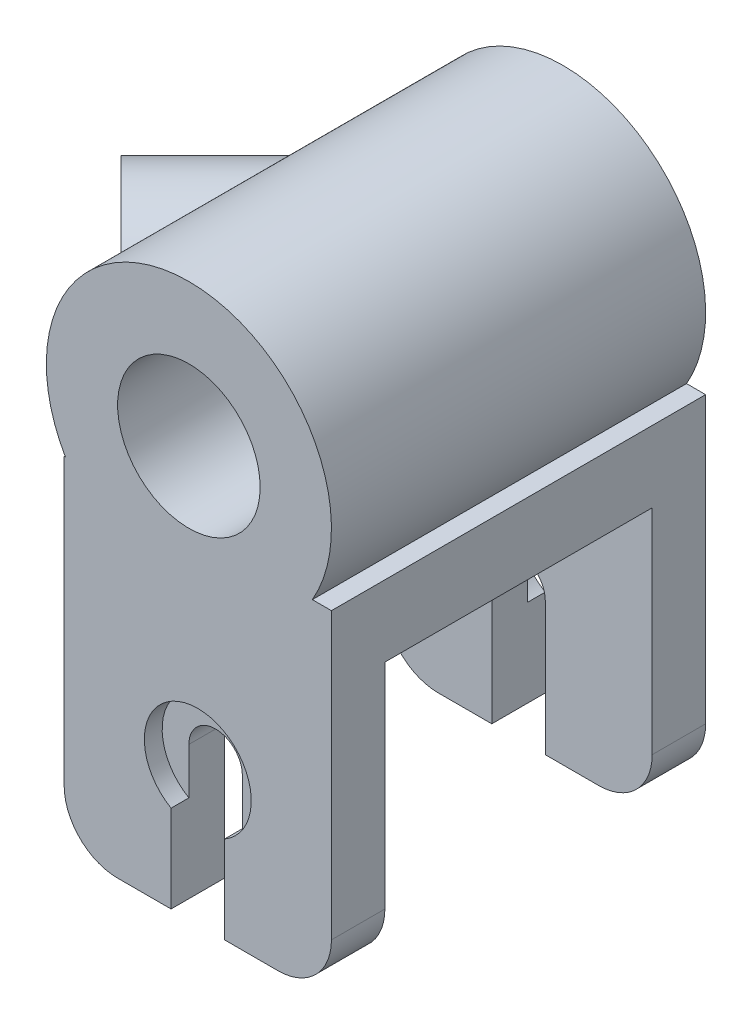
SolidWorks part; units mm, degrees
ref_plane "Спереди" through (0, 0, 0) normal (0, 0, 1) x (1, 0, 0)
ref_plane "Сверху" through (0, 0, 0) normal (0, 1, 0) x (1, 0, 0)
ref_plane "Справа" through (0, 0, 0) normal (1, 0, 0) x (0, 0, -1)
sketch "Sketch1" plane through (0, 0, 0) normal (0, 0, 1) x (1, 0, 0)
  line L0 (-7, -8) -> (8, -8)
  line L1 (-7, -4) -> (-6.9282, -4)
  line L2 (8, -8) -> (8, -4)
  line L3 (-7.3846, -3.0769) -> (-7, -4)
  line L4 (-7, -4) -> (-7, -8)
  line L5 (6.9282, -4) -> (8, -4)
  circle A0 centre (0, 0) radius 4
  arc A1 (6.9282, -4) -> (-6.9282, -4) centre (0, 0) ccw
  point P10 (-7.1344, -4)
  dimension "D1" = 8
  dimension "D2" = 4
  dimension "D3" = 15
extrude "Boss-Extrude1" add sketch "Sketch1" along normal blind 21 contours A1 L1 L4 L0 L2 L5 A0
sketch "Sketch3" plane through (0, -8, 0) normal (0, -1, 0) x (1, 0, 0)
  line L0 (-7, 21) -> (-7, 0) construction
  line L1 (8, 21) -> (-7, 21)
  line L2 (8, 21) -> (8, 18)
  line L3 (8, 18) -> (-7, 18)
  line L4 (-7, 21) -> (-7, 18)
  line L5 (8, 10.5) -> (2.9288, 10.5) construction
  line L6 (8, 21) -> (8, 0) construction
  line L7 (-7, 0) -> (-7, 3)
  line L8 (8, 3) -> (-7, 3)
  line L9 (8, 0) -> (8, 3)
  line L10 (8, 0) -> (-7, 0)
  dimension "D1" = 3
extrude "Boss-Extrude2" add sketch "Sketch3" along normal blind 15
sketch "Sketch4" plane through (0, 0, 21) normal (0, 0, 1) x (1, 0, 0)
  line L0 (0.5, -23) -> (0.5, -15.5) construction
  line L1 (8, -23) -> (-7, -23) construction
  line L2 (3.5, -15.5) -> (3.5, -23)
  line L3 (-2.5, -15.5) -> (-2.5, -23)
  line L4 (-2.5, -23) -> (3.5, -23)
  circle A0 centre (0.5, -15.5) radius 3
  dimension "D1" = 6
  dimension "D2" = 7.5
extrude "Cut-Extrude1" cut sketch "Sketch4" against normal blind 1
sketch "Sketch5" plane through (0, 0, 20) normal (0, 0, 1) x (1, 0, 0)
  line L0 (2, -15.5) -> (2, -23)
  line L1 (8, -23) -> (-7, -23) construction
  line L2 (-1, -15.5) -> (-1, -23)
  line L3 (-1, -23) -> (2, -23)
  circle A1 centre (0.5, -15.5) radius 1.5
  circle M6 centre (0.5, -15.5) radius 3
  dimension "D1" = 3
extrude "Cut-Extrude2" cut sketch "Sketch5" against normal blind 4 and the other way blind 4 contours A1 | A1 L2 L0 M6 | L2 L3 L0 M6
ref_plane "Plane1" through (0, 0, 10.5) normal (0, 0, 1) x (1, 0, 0)
mirror "Mirror1" about plane through (0, 0, 10.5) normal (0, 0, 1) of "Cut-Extrude2", "Cut-Extrude1"
fillet "Fillet1" radius 3 4 edges at (8, -23, 1.5) (-7, -23, 1.5) (-7, -23, 19.5) (8, -23, 19.5)
sketch "Sketch6" plane through (0, 0, 0) normal (0, 1, 0) x (1, 0, 0)
  line L0 (0, 0) -> (0, -25.5673) construction
  line L1 (0, -5) -> (-14.8681, -19.8681) construction
  line L2 (8, 0) -> (-8, 0) construction
  line L3 (-9.8995, -14.8995) -> (-6.364, -18.435)
  line L4 (-6.364, -18.435) -> (0, -12.0711)
  line L5 (0, -12.0711) -> (-3.5355, -8.5355)
  line L6 (-3.5355, -8.5355) -> (-9.8995, -14.8995)
  dimension "D1" = 45
  dimension "D2" = 5
  dimension "D3" = 5
  dimension "D4" = 14
revolve "Revolve1" add sketch "Sketch6" angle 360 about L1
sketch "Sketch7" plane through (0, 0, 21) normal (0, 0, 1) x (1, 0, 0)
  circle A0 centre (0, 0) radius 4
extrude "Cut-Extrude3" cut sketch "Sketch7" against normal blind 27
sketch "Sketch8" plane through (-12.3995, 0, 12.3995) normal (-0.7071, 0, 0.7071) x (0.7071, 0, 0.7071)
  circle A0 centre (3.5355, 0) radius 1.5
  dimension "D1" = 3
extrude "Cut-Extrude4" cut sketch "Sketch8" against normal blind 14
ref_plane "Plane2" through (-10.2782, 0, 10.2782) normal (-0.7071, 0, 0.7071) x (0.7071, 0, 0.7071)
sketch "Sketch9" plane through (-10.2782, 0, 10.2782) normal (-0.7071, 0, 0.7071) x (0.7071, 0, 0.7071)
  line L0 (1.919, 2.8) -> (-2.9261, 2.8)
  line L1 (6.7687, 0) -> (5.1521, 2.8)
  line L2 (5.1521, 2.8) -> (1.919, 2.8)
  line L3 (1.919, 2.8) -> (0.3024, 0)
  line L4 (0.3024, 0) -> (1.919, -2.8)
  line L5 (1.919, -2.8) -> (5.1521, -2.8)
  line L6 (5.1521, -2.8) -> (6.7687, 0)
  line L7 (1.919, -2.8) -> (-2.9261, -2.8)
  line L8 (-2.9261, -2.8) -> (-2.9261, 2.8)
  circle A0 centre (3.5355, 0) radius 2.8 construction
  point P1 (0, 0)
  point P11 (-2.7893, 2.8)
  point P16 (0, 0)
  dimension "D1" = 5.6
extrude "Cut-Extrude5" cut sketch "Sketch9" against normal blind 2.5 contours L5 L6 L1 L2 L3 L4 | L8 L7 L4 L3 L0
sketch "Sketch10" plane through (-12.3995, 0, 12.3995) normal (-0.7071, 0, 0.7071) x (0.7071, 0, 0.7071)
  circle A0 centre (3.5355, 0) radius 5
  dimension "D1" = 10
extrude "Cut-Extrude6" cut sketch "Sketch10" along normal blind 7.5
